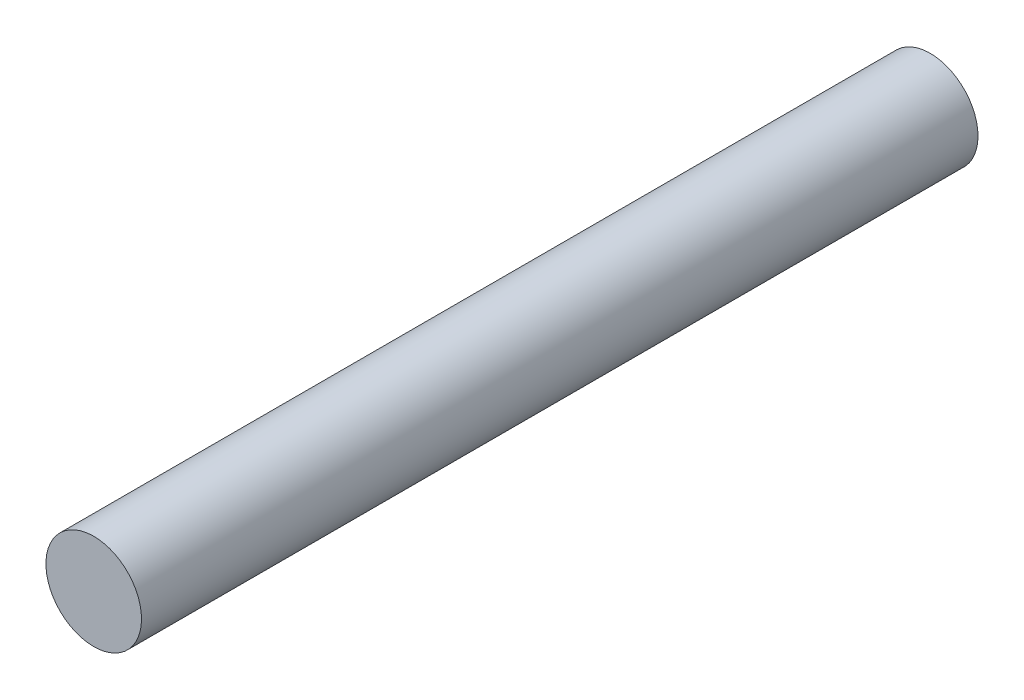
SolidWorks part; units mm, degrees
material "LW-PLA"
ref_plane "Front Plane" through (0, 0, 0) normal (0, 0, 1) x (1, 0, 0)
ref_plane "Top Plane" through (0, 0, 0) normal (0, 1, 0) x (1, 0, 0)
ref_plane "Right Plane" through (0, 0, 0) normal (1, 0, 0) x (0, 0, -1)
sketch "Sketch1" plane through (0, 0, 0) normal (0, 0, 1) x (1, 0, 0)
  circle A0 centre (0, 0) radius 1
  dimension "D1" = 2
extrude "Boss-Extrude1" add sketch "Sketch1" along normal blind 17.5
